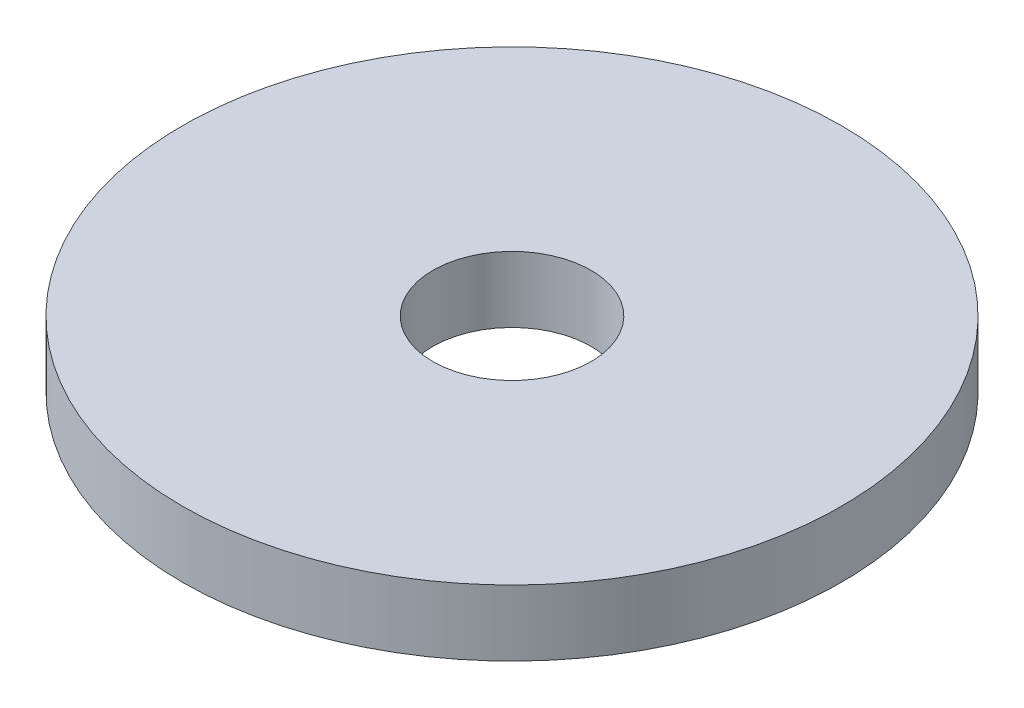
SolidWorks part; units mm, degrees
ref_plane "Спереди" through (0, 0, 0) normal (0, 0, 1) x (1, 0, 0)
ref_plane "Сверху" through (0, 0, 0) normal (0, 1, 0) x (1, 0, 0)
ref_plane "Справа" through (0, 0, 0) normal (1, 0, 0) x (0, 0, -1)
sketch "Эскиз1" plane through (0, 0, 0) normal (0, 1, 0) x (1, 0, 0)
  circle A0 centre (0, 0) radius 25
  circle A1 centre (0, 0) radius 6
  dimension "D1" = 50
  dimension "D2" = 12
extrude "Бобышка-Вытянуть1" add sketch "Эскиз1" along normal blind 5
